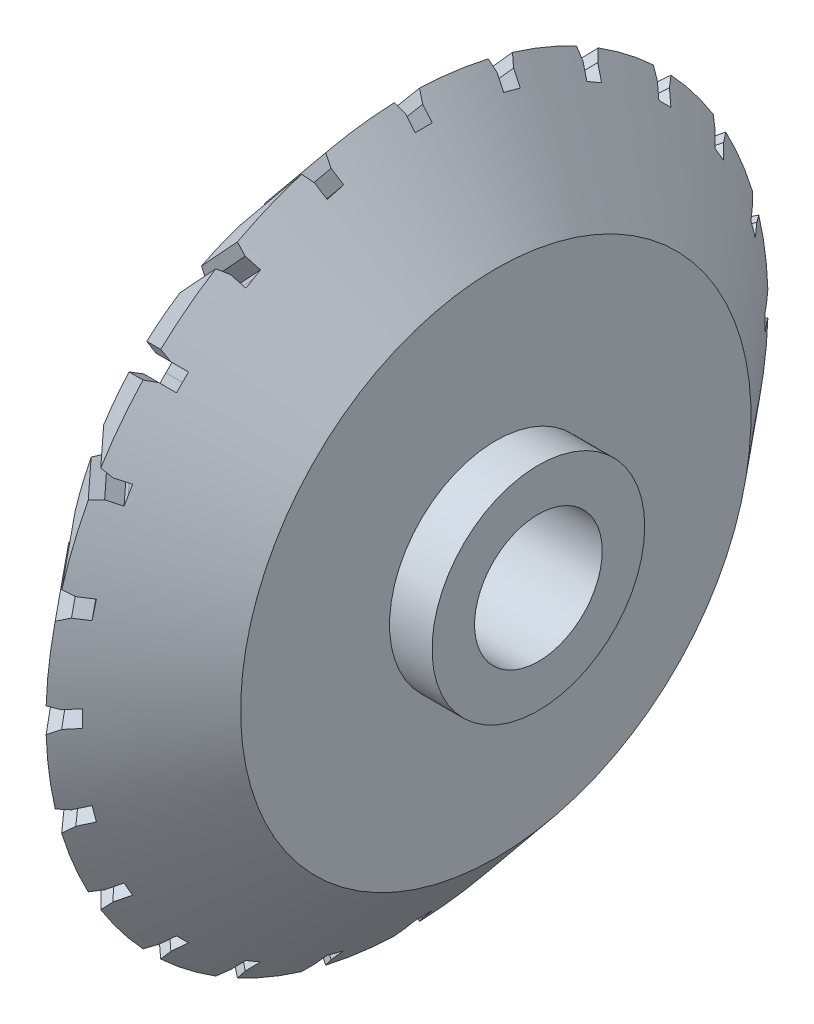
SolidWorks part; units mm, degrees
ref_plane "Alzado" through (0, 0, 0) normal (0, 0, 1) x (1, 0, 0)
ref_plane "Planta" through (0, 0, 0) normal (0, 1, 0) x (1, 0, 0)
ref_plane "Vista lateral" through (0, 0, 0) normal (1, 0, 0) x (0, 0, -1)
sketch "Croquis1" plane through (0, 0, 0) normal (0, 0, 1) x (1, 0, 0)
  line L0 (0, 0) -> (0, 1200)
  line L1 (0, 1200) -> (-417.8119, 1697.9289)
  line L2 (-417.8119, 1697.9289) -> (-835.6239, 1200)
  line L3 (-835.6239, 1200) -> (-835.6239, 0)
  line L4 (-835.6239, 0) -> (0, 0)
  dimension "D1" = 140
  dimension "D2" = 650
  dimension "D3" = 650
  dimension "D4" = 1200
revolve "Revolución4" add sketch "Croquis1" angle 360 about L4
sketch "Croquis6" plane through (0, 0, 0) normal (1, 0, 0) x (0, 0, -1)
  circle A0 centre (0, 0) radius 500
extrude "Saliente-Extruir2" add sketch "Croquis6" along normal blind 200
ref_plane "Plano1" through (590.8847, 495.8111, 0) normal (0.766, 0.6428, 0) x (0, 0, -1)
sketch "Croquis19" plane through (590.8847, 495.8111, 0) normal (0.766, 0.6428, 0) x (0, 0, -1)
  line L0 (0, 1569.2533) -> (0, 1318.4155) construction
  line L1 (-58.8111, 1568.4729) -> (-40, 1516.7898)
  line L2 (-40, 1516.7898) -> (-40, 1446.7898)
  line L3 (-40, 1446.7898) -> (0, 1446.7898)
  line L4 (0, 1446.7898) -> (40, 1446.7898)
  line L5 (40, 1446.7898) -> (40, 1516.7898)
  line L6 (40, 1516.7898) -> (58.8111, 1568.4729)
  line L7 (58.8111, 1568.4729) -> (66.5582, 1589.7579)
  line L8 (-58.8111, 1568.4729) -> (-70.8059, 1589.7579)
  line L9 (-70.8059, 1589.7579) -> (66.5582, 1589.7579)
  ellipse E0 centre (0, 268.5643) end of major axis (1697.9289, 268.5643) minor radius 1300.689 construction
  dimension "D1" = 160
  dimension "D2" = 55
  dimension "D3" = 40
  dimension "D4" = 70
ref_plane "Plano8" through (-1081.2489, 907.2755, 0) normal (-0.766, 0.6428, 0) x (0, 0, 1)
sketch "Croquis22" plane through (-1081.2489, 907.2755, 0) normal (-0.766, 0.6428, 0) x (0, 0, 1)
  line L0 (0, 0) -> (0, 1032.1246)
sweep "Cortar-Barrer3" cut profiles "Croquis19" path "Croquis22"
pattern_circular "MatrizC1" count 24 every 15 about axis through (0, 0, 0) along (1, 0, 0) of "Cortar-Barrer3"
sketch "Croquis23" plane through (-835.6239, 0, 0) normal (-1, 0, 0) x (0, 0, 1)
  circle A0 centre (0, 0) radius 800
extrude "Cortar-Extruir1" cut sketch "Croquis23" against normal blind 101
sketch "Croquis24" plane through (200, 0, 0) normal (1, 0, 0) x (0, 0, -1)
  circle A0 centre (0, 0) radius 300
extrude "Cortar-Extruir2" cut sketch "Croquis24" against normal blind 1910
